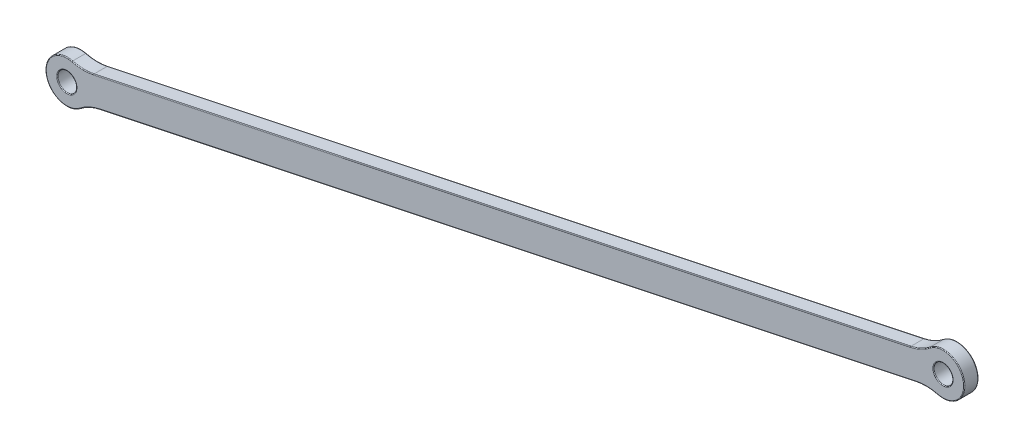
SolidWorks part; units mm, degrees
ref_plane "Front Plane" through (0, 0, 0) normal (0, 0, 1) x (1, 0, 0)
ref_plane "Top Plane" through (0, 0, 0) normal (0, 1, 0) x (1, 0, 0)
ref_plane "Right Plane" through (0, 0, 0) normal (1, 0, 0) x (0, 0, -1)
sketch "Sketch1" plane through (0, 0, 0) normal (0, 0, 1) x (1, 0, 0)
  line L1 (-24.9494, 236.3313) -> (-210.4552, 197.1426) construction
  line L2 (-210.4552, 197.1426) -> (-24.9494, 236.3313) construction
  line L3 (-207.7936, 200.7711) -> (-28.8512, 238.5733)
  line L4 (-206.5535, 194.9007) -> (-27.611, 232.7029)
  arc A2 (-207.7936, 200.7711) -> (-206.5535, 194.9007) centre (-210.4552, 197.1426) ccw
  arc A3 (-27.611, 232.7029) -> (-28.8512, 238.5733) centre (-24.9494, 236.3313) ccw
  circle A6 centre (-210.4552, 197.1426) radius 2
  circle A7 centre (-24.9494, 236.3313) radius 2
  point P3 (-117.7023, 216.737)
  dimension "D2" = 9
  dimension "D4" = 4
  dimension "D5" = 4
  dimension "D1" = 6
  dimension "D3" = 189.6
extrude "Boss-Extrude1" add sketch "Sketch1" against normal blind 3
fillet "Fillet1" radius 10 4 edges at (-28.8512, 238.5733, -1.5) (-27.611, 232.7029, -1.5) (-206.5535, 194.9007, -1.5) (-207.7936, 200.7711, -1.5)
fillet "Fillet2" radius 0.15 20 edges at (-205.7222, 194.8084, -3) (-205.7222, 194.8084, 0) (-117.0822, 213.8018, -3) (-117.0822, 213.8018, 0) (-28.3339, 232.2823, -3) (-28.3339, 232.2823, 0) (-20.5466, 237.2615, -3) (-20.5466, 237.2615, 0) (-29.6824, 238.6655, -3) (-29.6824, 238.6655, 0) (-118.3224, 219.6722, 0) (-118.3224, 219.6722, -3) (-207.0707, 201.1917, -3) (-207.0707, 201.1917, 0) (-214.858, 196.2125, -3) (-214.858, 196.2125, 0) (-208.4552, 197.1426, -3) (-208.4552, 197.1426, 0) (-22.9494, 236.3313, -3) (-22.9494, 236.3313, 0)
